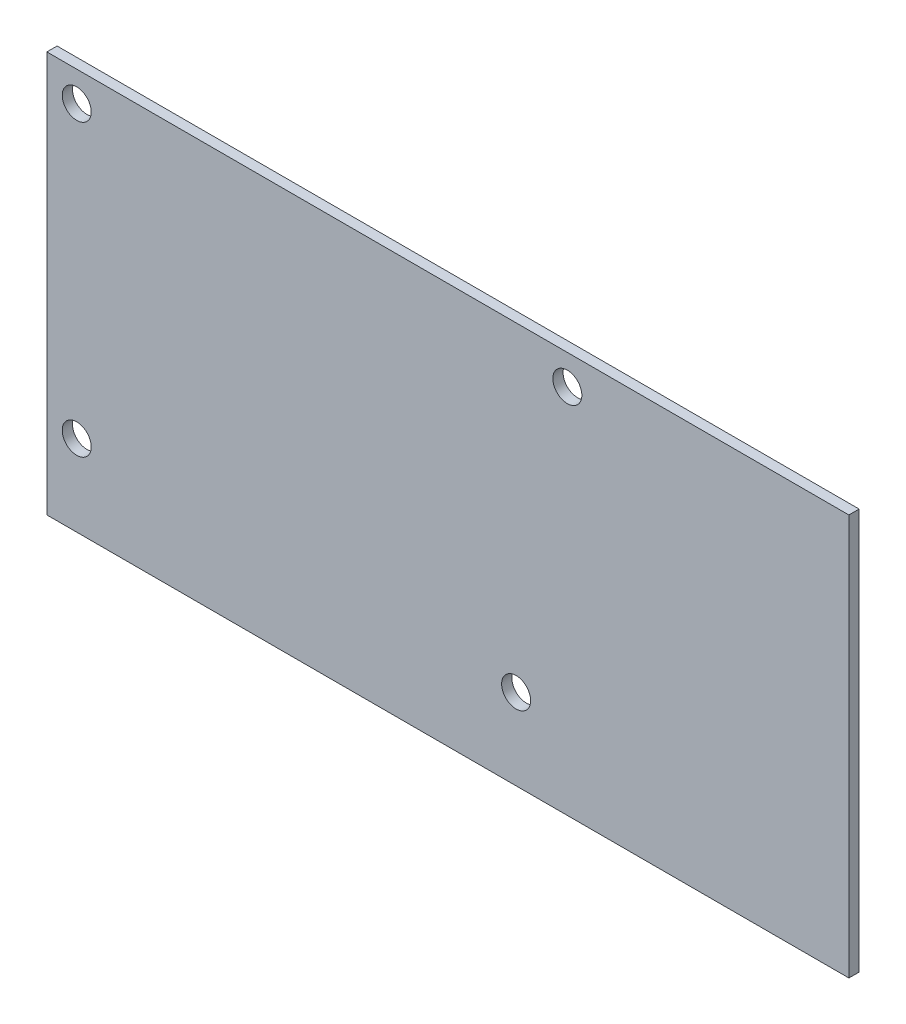
SolidWorks part; units mm, degrees
material "A-Glass Fiber"
ref_plane "Front Plane" through (0, 0, 0) normal (0, 0, 1) x (1, 0, 0)
ref_plane "Top Plane" through (0, 0, 0) normal (0, 1, 0) x (1, 0, 0)
ref_plane "Right Plane" through (0, 0, 0) normal (1, 0, 0) x (0, 0, -1)
sketch "Sketch1" plane through (0, 0, 0) normal (0, 0, 1) x (1, 0, 0)
  line L0 (47, -23.5) -> (-47, 23.5) construction
  line L1 (-47, 23.5) -> (47, 23.5)
  line L2 (-47, 23.5) -> (-47, -23.5)
  line L3 (-47, -23.5) -> (47, -23.5)
  line L4 (47, 23.5) -> (47, -23.5)
  point P0 (0, 0)
  dimension "D1" = 47
  dimension "D2" = 94
extrude "Boss-Extrude1" add sketch "Sketch1" along normal blind 1.2
sketch "Sketch2" plane through (0, 0, 1.2) normal (0, 0, 1) x (1, 0, 0)
  line L1 (-47, -23.5) -> (47, -23.5) construction
  line L4 (-43.5, -17.5) -> (-43.5, 23.5) construction
  line L5 (-47, 23.5) -> (-47, -23.5) construction
  line L6 (8, -14) -> (-43.5, -14) construction
  line L8 (-47, 23.5) -> (47, 23.5) construction
  circle A0 centre (-43.5, -14) radius 3.5 construction
  circle A1 centre (-43.5, 20) radius 3.5 construction
  circle A2 centre (14, 20) radius 3.5 construction
  circle A3 centre (8, -14) radius 3.5 construction
  circle A4 centre (14, 20) radius 1.7
  circle A5 centre (8, -14) radius 1.7
  circle A6 centre (-43.5, -14) radius 1.7
  circle A7 centre (-43.5, 20) radius 1.7
  dimension "D2" = 7
  dimension "D1" = 3.4
  dimension "D3" = 14
  dimension "D4" = 9.5
  dimension "D5" = 8
extrude "Cut-Extrude1" cut sketch "Sketch2" against normal up to next
